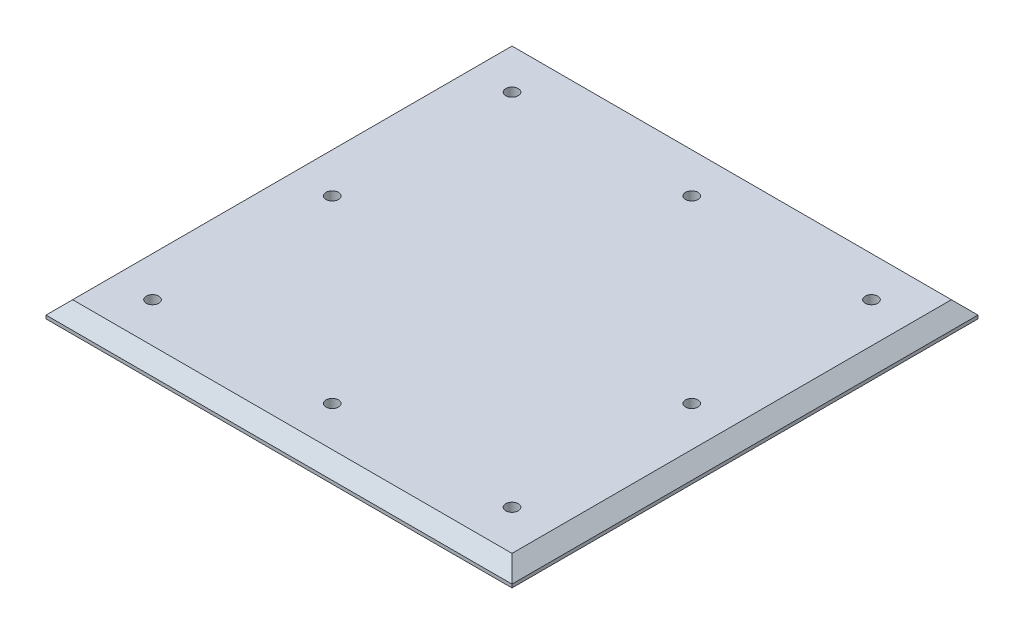
SolidWorks part; units mm, degrees
ref_plane "Front Plane" through (0, 0, 0) normal (0, 0, 1) x (1, 0, 0)
ref_plane "Top Plane" through (0, 0, 0) normal (0, 1, 0) x (1, 0, 0)
ref_plane "Right Plane" through (0, 0, 0) normal (1, 0, 0) x (0, 0, -1)
sketch "Sketch1" plane through (0, 0, 0) normal (0, 1, 0) x (1, 0, 0)
  line L1 (0, 0) -> (177.8, 0)
  line L2 (0, 0) -> (0, 177.8)
  line L3 (0, 177.8) -> (177.8, 177.8)
  line L4 (177.8, 0) -> (177.8, 177.8)
  circle A0 centre (20.32, 157.48) radius 2.3813
  circle A1 centre (88.9, 157.48) radius 2.3813
  circle A2 centre (157.48, 157.48) radius 2.3813
  circle A3 centre (20.32, 88.9) radius 2.3813
  circle A4 centre (20.32, 20.32) radius 2.3813
  circle A5 centre (88.9, 20.32) radius 2.3813
  circle A6 centre (157.48, 88.9) radius 2.3813
  circle A7 centre (157.48, 20.32) radius 2.3813
  dimension "D3" = 4.7625
  dimension "D6" = 20.32
  dimension "D12" = 20.32
  dimension "D1" = 177.8
  dimension "D2" = 177.8
  dimension "D4" = 20.32
  dimension "D5" = 20.32
  dimension "D7" = 20.32
  dimension "D8" = 20.32
  dimension "D9" = 20.32
  dimension "D10" = 20.32
  dimension "D11" = 20.32
  dimension "D13" = 20.32
  dimension "D14" = 20.32
  dimension "D15" = 20.32
extrude "Boss-Extrude1" add sketch "Sketch1" along normal blind 6.35
chamfer "Chamfer1" distance 5.08 angle 45 4 edges at (88.9, 6.35, -177.8) (0, 6.35, -88.9) (177.8, 6.35, -88.9) (88.9, 6.35, 0)
